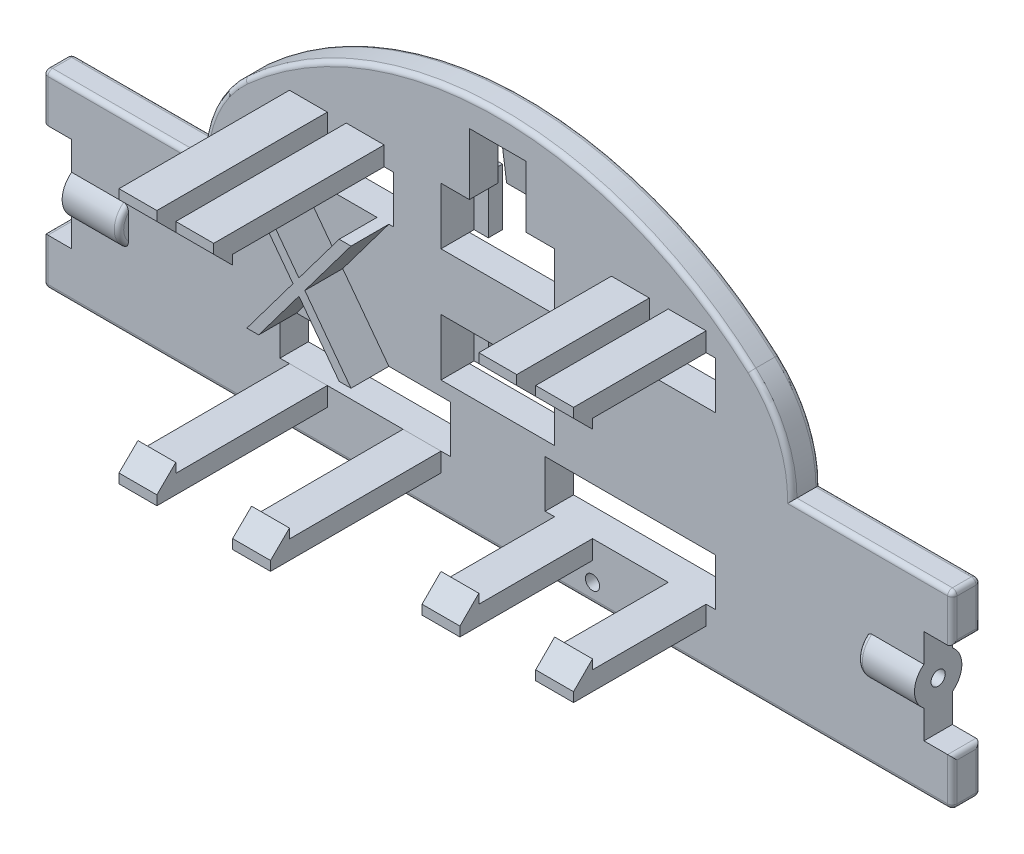
SolidWorks part; units mm, degrees
ref_plane "Plan de face" through (0, 0, 0) normal (0, 0, 1) x (1, 0, 0)
ref_plane "Plan de dessus" through (0, 0, 0) normal (0, 1, 0) x (1, 0, 0)
ref_plane "Plan de droite" through (0, 0, 0) normal (1, 0, 0) x (0, 0, -1)
sketch "Esquisse1" plane through (0, 0, 0) normal (0, 0, 1) x (1, 0, 0)
  line L0 (-48, 20) -> (-48, 40)
  line L1 (0, 0) -> (-48, 0)
  line L2 (0, 0) -> (0, 5)
  line L3 (0, 20) -> (-16.9072, 20)
  line L4 (-48, 0) -> (-48, 20)
  line L5 (0, 15) -> (0, 20)
  line L6 (0, 15) -> (-3, 15)
  line L8 (0, 5) -> (-3, 5)
  line L9 (-3, 15) -> (-3, 5)
  arc A0 (-21.2414, 29.7318) -> (-48, 40) centre (-48, 0) ccw
  arc A1 (-16.9072, 20) -> (-21.2414, 29.7318) centre (-30, 20) ccw
  point P5 (-18.8097, 13.2032)
  dimension "D4" = 80
  dimension "D1" = 20
  dimension "D2" = 48
  dimension "D3" = 20
  dimension "D5" = 10
  dimension "D6" = 5
  dimension "D7" = 3
extrude "Boss.-Extru.1" add sketch "Esquisse1" along normal blind 3
sketch "Esquisse2" plane through (-3, 0, 0) normal (1, 0, 0) x (0, 0, -1)
  line L0 (0, 5) -> (0, 15) construction
  line L1 (-3, 5) -> (0, 5) construction
  circle A0 centre (-1.5, 10) radius 2.5
  dimension "D1" = 5
  dimension "D2" = 1.5
  dimension "D3" = 5
extrude "Boss.-Extru.2" add sketch "Esquisse2" against normal blind 6
sketch "Esquisse3" plane through (-3, 0, 0) normal (1, 0, 0) x (0, 0, -1)
  circle A0 centre (-1.5, 10) radius 0.75
  arc A1 (0, 8) -> (0, 12) centre (-1.5, 10) ccw construction
  dimension "D1" = 1.5
extrude "Enlèv. mat.-Extru.1" cut sketch "Esquisse3" against normal blind 6
sketch "Esquisse4" plane through (0, 0, 3) normal (0, 0, 1) x (1, 0, 0)
  line L0 (0, 0) -> (0, 5) construction
  line L1 (-48, 0) -> (0, 0) construction
  line L2 (0, 15) -> (0, 20) construction
  line L3 (-43, 11) -> (-25, 11)
  line L4 (-43, 11) -> (-43, 6)
  line L5 (-43, 6) -> (-25, 6)
  line L6 (-25, 11) -> (-25, 6)
  line L7 (-37, 29) -> (-25, 29)
  line L8 (-37, 29) -> (-37, 24)
  line L9 (-37, 24) -> (-25, 24)
  line L10 (-25, 29) -> (-25, 24)
  line L11 (-52.0438, 30.5) -> (-42, 30.5)
  line L12 (-52.0438, 30.5) -> (-52.0438, 24.5)
  line L13 (-52.0438, 24.5) -> (-42, 24.5)
  line L14 (-42, 30.5) -> (-42, 24.5)
  line L15 (-52.7546, 18.5) -> (-42, 18.5)
  line L16 (-52.7546, 18.5) -> (-52.7546, 12.5)
  line L17 (-52.7546, 12.5) -> (-42, 12.5)
  line L18 (-42, 18.5) -> (-42, 12.5)
  line L19 (-51, 37) -> (-45, 37)
  line L20 (-51, 37) -> (-51, 29.9753)
  line L21 (-51, 29.9753) -> (-45, 29.9753)
  line L22 (-45, 37) -> (-45, 29.9753)
  line L23 (-48, 40) -> (-48, 0) construction
  circle A0 centre (-38, 2) radius 0.75
  line M10 (-48, 40) -> (-48, 0)
  dimension "D1" = 1.5
  dimension "D2" = 38
  dimension "D3" = 2
  dimension "D4" = 18
  dimension "D5" = 5
  dimension "D6" = 6
  dimension "D7" = 25
  dimension "D8" = 5
  dimension "D9" = 12
  dimension "D10" = 24
  dimension "D11" = 25
  dimension "D12" = 6
  dimension "D13" = 6
  dimension "D14" = 12.5
  dimension "D15" = 6
  dimension "D16" = 6
  dimension "D17" = 6
  dimension "D18" = 6
  dimension "D19" = 3
  dimension "D20" = 37
extrude "Enlèv. mat.-Extru.2" cut sketch "Esquisse4" against normal through all contours L11 L22 L21 L13 L14 M10 | L22 L19 L11 M10 | L10 L7 L8 L9 | L18 L15 L17 M10 | L6 L3 L4 L5 | A0 | L22 L11 L21 M10
sketch "Esquisse5" plane through (0, 12.5, 0) normal (0, 1, 0) x (1, 0, 0)
  line L0 (-40.5, 0) -> (-40.5, 2)
  line L1 (-40.5, 2) -> (-43.5, 2)
  line L2 (-43.5, 2) -> (-43.5, 0.5)
  line L3 (-43.5, 0.5) -> (-42, 0.5)
  line L4 (-42, 0.5) -> (-42, 0)
  line L5 (-48, 0) -> (-42, 0) construction
  line L6 (-42, 0) -> (-40.5, 0)
  dimension "D1" = 1.5
  dimension "D2" = 2
  dimension "D3" = 3
  dimension "D4" = 1.5
extrude "Boss.-Extru.3" add sketch "Esquisse5" along normal up to surface (6 mm away) up to face at (-45, 18.5, 1.5)
sketch "Esquisse6" plane through (0, 24.5, 0) normal (0, 1, 0) x (1, 0, 0)
  line L0 (-42, 0) -> (-42, 0.5)
  line L1 (-42, 0.5) -> (-43.5, 0.5)
  line L2 (-43.5, 0.5) -> (-43.5, 2)
  line L3 (-43.5, 2) -> (-40.5, 2)
  line L4 (-40.5, 2) -> (-40.5, 0)
  line L5 (-40.5, 0) -> (-42, 0)
  dimension "D1" = 3
  dimension "D2" = 1.5
  dimension "D3" = 2
  dimension "D4" = 1.5
extrude "Boss.-Extru.4" add sketch "Esquisse6" along normal up to surface (6 mm away) up to face at (-43.5, 30.5, 1.5)
sketch "Esquisse7" plane through (-25, 0, 0) normal (-1, 0, 0) x (0, 0, 1)
  line L0 (3, 6) -> (15, 6)
  line L1 (0, 6) -> (3, 6) construction
  line L2 (15, 6) -> (15, 7)
  line L3 (15, 7) -> (17, 5)
  line L4 (17, 5) -> (17, 4)
  line L5 (17, 4) -> (3, 4)
  line L6 (3, 4) -> (3, 6)
  line L7 (3, 11) -> (3, 6) construction
  dimension "D1" = 14
  dimension "D2" = 2
  dimension "D3" = 1
  dimension "D4" = 1
  dimension "D5" = 2
extrude "Boss.-Extru.5" add sketch "Esquisse7" along normal blind 4 from offset 1
sketch "Esquisse8" plane through (-43, 0, 0) normal (1, 0, 0) x (0, 0, -1)
  line L0 (-3, 6) -> (-3, 4)
  line L1 (-17, 4) -> (-17, 5) construction
  line L2 (-17, 5) -> (-15, 7) construction
  line L3 (-15, 7) -> (-15, 6) construction
  line L4 (-15, 6) -> (-3, 6) construction
  line L5 (-17, 4) -> (-17, 5)
  line L6 (-17, 5) -> (-15, 7)
  line L7 (-15, 7) -> (-15, 6)
  line L8 (-15, 6) -> (-3, 6)
  line L9 (-17, 4) -> (-3, 4)
extrude "Boss.-Extru.6" add sketch "Esquisse8" along normal blind 4 from offset 1
sketch "Esquisse9" plane through (-25, 0, 0) normal (-1, 0, 0) x (0, 0, 1)
  line L0 (3, 29) -> (15, 29)
  line L1 (15, 29) -> (15, 28)
  line L2 (15, 28) -> (17, 30)
  line L3 (17, 30) -> (17, 31)
  line L4 (17, 31) -> (3, 31)
  line L5 (3, 31) -> (3, 29)
  dimension "D1" = 14
  dimension "D2" = 1
  dimension "D3" = 1
  dimension "D4" = 2
  dimension "D5" = 2
extrude "Boss.-Extru.7" add sketch "Esquisse9" along normal blind 4 from offset 1
sketch "Esquisse10" plane through (-37, 0, 0) normal (1, 0, 0) x (0, 0, -1)
  line L0 (-3, 29) -> (-3, 31)
  line L1 (-17, 31) -> (-3, 31) construction
  line L2 (-17, 30) -> (-17, 31) construction
  line L3 (-15, 28) -> (-17, 30) construction
  line L4 (-15, 29) -> (-15, 28) construction
  line L5 (-3, 29) -> (-15, 29) construction
  line L6 (-17, 31) -> (-3, 31)
  line L7 (-17, 30) -> (-17, 31)
  line L8 (-15, 28) -> (-17, 30)
  line L9 (-15, 29) -> (-15, 28)
  line L10 (-3, 29) -> (-15, 29)
extrude "Boss.-Extru.8" add sketch "Esquisse10" along normal blind 4 from offset 1
mirror "Symétrie1" about plane through (-48, 0, 3) normal (1, 0, 0) of "Boss.-Extru.1", "Enlèv. mat.-Extru.1", "Boss.-Extru.2", "Enlèv. mat.-Extru.2", "Boss.-Extru.3", "Boss.-Extru.4"
sketch "Esquisse13" plane through (-53, 0, 0) normal (-1, 0, 0) x (0, 0, 1)
  line L0 (3, 6) -> (3, 4)
  line L1 (3, 4) -> (21, 4)
  line L2 (21, 4) -> (21, 5)
  line L3 (21, 5) -> (19, 6.9662)
  line L4 (19, 6.9662) -> (19, 5.9662)
  line L5 (19, 5.9662) -> (3, 6)
  dimension "D1" = 18
  dimension "D2" = 16
  dimension "D3" = 1
  dimension "D4" = 1
  dimension "D5" = 2
extrude "Boss.-Extru.9" add sketch "Esquisse13" along normal blind 4 from offset 1
sketch "Esquisse14" plane through (-71, 0, 0) normal (1, 0, 0) x (0, 0, -1)
  line L0 (-3, 6) -> (-3, 4)
  line L1 (-3, 4) -> (-21, 4) construction
  line L2 (-21, 4) -> (-21, 5) construction
  line L3 (-21, 5) -> (-19, 6.9662) construction
  line L4 (-19, 6.9662) -> (-19, 5.9662) construction
  line L5 (-19, 5.9662) -> (-3, 6) construction
  line L6 (-3, 4) -> (-21, 4)
  line L7 (-21, 4) -> (-21, 5)
  line L8 (-21, 5) -> (-19, 6.9662)
  line L9 (-19, 6.9662) -> (-19, 5.9662)
  line L10 (-19, 5.9662) -> (-3, 6)
extrude "Boss.-Extru.10" add sketch "Esquisse14" along normal blind 4 from offset 1
sketch "Esquisse16" plane through (-59, 0, 0) normal (-1, 0, 0) x (0, 0, 1)
  line L0 (3, 29) -> (19, 29)
  line L1 (19, 29) -> (19, 28)
  line L2 (19, 28) -> (21, 30)
  line L3 (21, 30) -> (21, 31)
  line L4 (21, 31) -> (3, 31)
  line L5 (3, 31) -> (3, 29)
  dimension "D1" = 2
  dimension "D2" = 1
  dimension "D3" = 1
  dimension "D4" = 2
  dimension "D5" = 18
extrude "Boss.-Extru.11" add sketch "Esquisse16" along normal blind 4 from offset 1
sketch "Esquisse17" plane through (-71, 0, 0) normal (1, 0, 0) x (0, 0, -1)
  line L0 (-3, 29) -> (-3, 31)
  line L1 (-3, 29) -> (-19, 29) construction
  line L2 (-19, 29) -> (-19, 28) construction
  line L3 (-19, 28) -> (-21, 30) construction
  line L4 (-21, 30) -> (-21, 31) construction
  line L5 (-21, 31) -> (-3, 31) construction
  line L6 (-3, 29) -> (-19, 29)
  line L7 (-19, 29) -> (-19, 28)
  line L8 (-19, 28) -> (-21, 30)
  line L9 (-21, 30) -> (-21, 31)
  line L10 (-21, 31) -> (-3, 31)
extrude "Boss.-Extru.12" add sketch "Esquisse17" along normal blind 4 from offset 1
sketch "Esquisse18" plane through (0, 0, 3) normal (0, 0, 1) x (1, 0, 0)
  line L0 (-59.5, 24) -> (-64.375, 17.5)
  line L1 (-59, 24) -> (-71, 24) construction
  line L2 (-53, 11) -> (-71, 11) construction
  line L3 (-69.25, 11) -> (-70.5, 11)
  line L4 (-70.5, 11) -> (-65.625, 17.5)
  line L5 (-60.75, 24) -> (-59.5, 24)
  line L6 (-70.5, 24) -> (-65.625, 17.5)
  line L7 (-60.75, 11) -> (-59.5, 11)
  line L8 (-59.5, 11) -> (-64.375, 17.5)
  line L9 (-69.25, 24) -> (-70.5, 24)
  line L10 (-65, 18.3333) -> (-60.75, 24)
  line L11 (-65, 16.6667) -> (-60.75, 11)
  line L12 (-65, 18.3333) -> (-69.25, 24)
  line L13 (-65, 16.6667) -> (-69.25, 11)
  dimension "D1" = 1
  dimension "D2" = 1
  dimension "D3" = 0.5
  dimension "D4" = 0.5
  dimension "D5" = 0.5
extrude "Boss.-Extru.13" add sketch "Esquisse18" along normal blind 4
sketch "Esquisse19" plane through (-45, 0, 0) normal (-1, 0, 0) x (0, 0, 1)
  line L0 (0.8, 37) -> (0.0688, 31.0447)
  line L1 (0.0688, 31.0447) -> (-0.7312, 31.0447)
  line L3 (-0.7312, 31.0447) -> (0, 37)
  line L5 (0, 37) -> (0.8, 37)
  line L6 (3, 37) -> (3, 30.5) construction
  dimension "D1" = 0.8
  dimension "D2" = 6
  dimension "D3" = 7
extrude "Boss.-Extru.14" add sketch "Esquisse19" along normal blind 4 from offset 1
fillet "Congé1" radius 0.5 32 edges at (-48, 0, 0) (-48, 0, 3) (0, 0, 1.5) (0, 2.5, 0) (0, 2.5, 3) (0, 5, 1.5) (0, 15, 1.5) (0, 17.5, 0) (0, 17.5, 3) (0, 20, 1.5) (-8.4536, 20, 0) (-8.4536, 20, 3) (-18.0398, 25.3266, 0) (-18.0398, 25.3266, 3) (-77.9602, 25.3266, 0) (-77.9602, 25.3266, 3) (-96, 5, 1.5) (-96, 15, 1.5) (-96, 20, 1.5) (-96, 0, 1.5) (-96, 2.5, 0) (-96, 2.5, 3) (-96, 17.5, 0) (-96, 17.5, 3) (-87.5464, 20, 0) (-87.5464, 20, 3) (-48, 40, 0) (-48, 40, 3) (-87, 10, 4) (-9, 10, 4) (-87, 10, -1) (-9, 10, -1)
